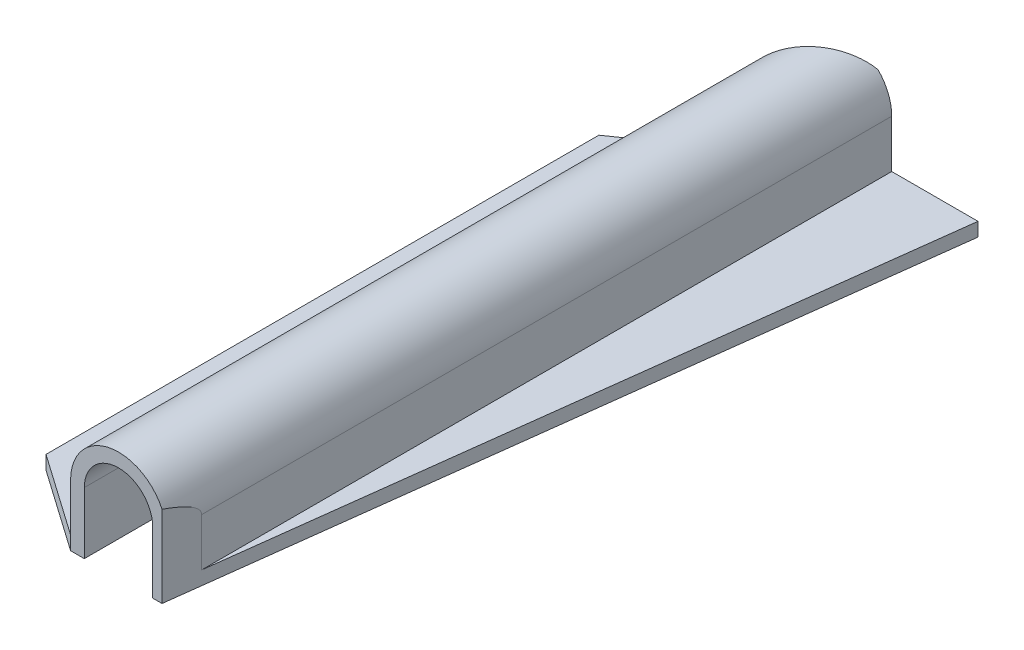
SolidWorks part; units mm, degrees
material "ABS"
ref_plane "Plan de face" through (0, 0, 0) normal (0, 0, 1) x (1, 0, 0)
ref_plane "Plan de dessus" through (0, 0, 0) normal (0, 1, 0) x (1, 0, 0)
ref_plane "Plan de droite" through (0, 0, 0) normal (1, 0, 0) x (0, 0, -1)
sketch "Esquisse1" plane through (0, 0, 0) normal (0, 0, 1) x (1, 0, 0)
  line L0 (-9.5, 0) -> (-2.5, 0)
  line L1 (-2.5, 0) -> (-2.5, 4.5)
  line L2 (2.5, 4.5) -> (2.5, 0)
  line L3 (2.5, 0) -> (17.5, 0)
  line L4 (-2.5, 0) -> (2.5, 0) construction
  arc A0 (-2.5, 4.5) -> (2.5, 4.5) centre (0, 4.5) cw
  dimension "D1" = 5
  dimension "D3" = 7
  dimension "D2" = 7
  dimension "D4" = 15
extrude "Extru.-Mince1" add sketch "Esquisse1" along normal blind 53 thin thin type one direction reverse wall 1
sketch "Esquisse2" plane through (0, 0, 0) normal (0, 1, 0) x (1, 0, 0)
  line L0 (2.5, 0) -> (-9.5, -8.4025)
  line L1 (-9.5, -53) -> (-9.5, 0) construction
  line L2 (-9.5, -8.4025) -> (-9.5, 0)
  line L3 (-9.5, 0) -> (2.5, 0)
  line L4 (3.5, 0) -> (17.5, 0) construction
  line L5 (17.5, -53) -> (17.5, 61.5747)
  line L6 (1.8407, -82.2391) -> (12.756, 5.0813) construction
  line L7 (17.5, -53) -> (17.5, 0) construction
  line L8 (17.5, 61.5747) -> (3.1778, -53)
  line L9 (3.5, -53) -> (17.5, -53) construction
  line L10 (3.1778, -53) -> (17.5, -53)
  line L11 (-0.1439, -81.991) -> (10.7715, 5.3294) construction
  line L12 (-9.5, -48.7988) -> (-9.5, -53)
  line L13 (-9.5, -53) -> (-3.5, -53)
  line L14 (-3.5, -53) -> (-9.5, -48.7988)
  line L15 (-9.5, -53) -> (-9.5, 0) construction
  line L16 (-9.5, -53) -> (-3.5, -53) construction
  dimension "D1" = 35
  dimension "D2" = 0.3
  dimension "D3" = 35
extrude "Enlèv. mat.-Extru.1" cut sketch "Esquisse2" along normal through all
sketch "Esquisse3" plane through (0, 1, 0) normal (0, 1, 0) x (1, 0, 0)
  line L0 (-7, -28.6006) -> (-9.5, -28.6006) construction
  line L1 (-9.5, -48.7988) -> (-9.5, -8.4025) construction
  circle A0 centre (-7, -28.6006) radius 1.1
  dimension "D1" = 2.2
  dimension "D2" = 2.5
extrude "Enlèv. mat.-Extru.2" cut sketch "Esquisse3" against normal through all
